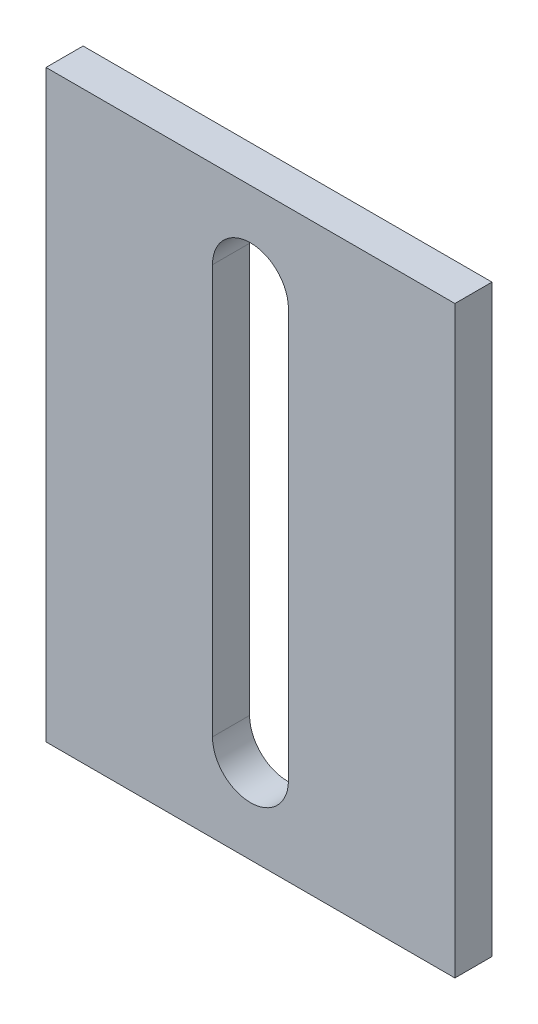
SolidWorks part; units mm, degrees
ref_plane "Alzado" through (0, 0, 0) normal (0, 0, 1) x (1, 0, 0)
ref_plane "Planta" through (0, 0, 0) normal (0, 1, 0) x (1, 0, 0)
ref_plane "Vista lateral" through (0, 0, 0) normal (1, 0, 0) x (0, 0, -1)
sketch "Croquis1" plane through (0, 0, 0) normal (0, 0, 1) x (1, 0, 0)
  line L0 (0, -35) -> (0, 35) construction
  line L1 (35, -50) -> (-35, -50)
  line L2 (35, -50) -> (35, 50)
  line L3 (35, 50) -> (-35, 50)
  line L4 (-35, -50) -> (-35, 50)
  line L5 (35, -50) -> (-35, 50) construction
  line L6 (35, 50) -> (-35, -50) construction
  line L7 (-6.5, -35) -> (-6.5, 35)
  line L8 (6.5, -35) -> (6.5, 35)
  arc A0 (-6.5, -35) -> (6.5, -35) centre (0, -35) ccw
  arc A1 (6.5, 35) -> (-6.5, 35) centre (0, 35) ccw
  point P0 (0, 0)
  point P8 (0, 0)
  dimension "D3" = 6.5
  dimension "D1" = 70
  dimension "D2" = 100
  dimension "D4" = 70
extrude "Saliente-Extruir1" add sketch "Croquis1" along normal blind 6.35
